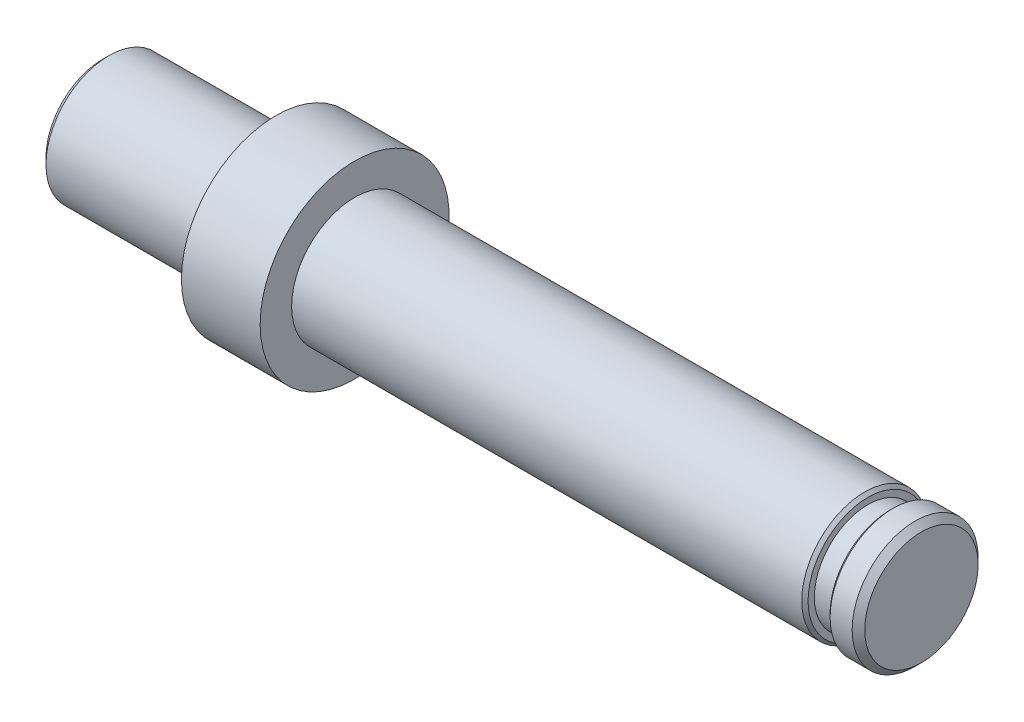
SolidWorks part; units mm, degrees
ref_plane "Спереди" through (0, 0, 0) normal (0, 0, 1) x (1, 0, 0)
ref_plane "Сверху" through (0, 0, 0) normal (0, 1, 0) x (1, 0, 0)
ref_plane "Справа" through (0, 0, 0) normal (1, 0, 0) x (0, 0, -1)
sketch "Эскиз1" plane through (0, 0, 0) normal (0, 0, 1) x (1, 0, 0)
  line L0 (0, 0) -> (26, 0)
  line L1 (26, 0) -> (26, 2)
  line L2 (26, 2) -> (25, 2)
  line L3 (25, 2) -> (25, 1.7)
  line L4 (25, 1.7) -> (24.3, 1.7)
  line L5 (24.3, 1.7) -> (24.3, 2)
  line L6 (24.3, 2) -> (8, 2)
  line L7 (8, 2) -> (8, 3)
  line L8 (8, 3) -> (5.5, 3)
  line L9 (5.5, 3) -> (5.5, 2)
  line L10 (5.5, 2) -> (0, 2)
  line L11 (0, 2) -> (0, 0)
  point P9 (22.1191, 1.3889)
  point P14 (22.1191, 0.8408)
  point P15 (22.775, 0.8408)
  point P16 (22.775, 1.3889)
  dimension "D1" = 2
  dimension "D2" = 5.5
  dimension "D3" = 3
  dimension "D4" = 1
  dimension "D5" = 2
  dimension "D6" = 2
  dimension "D7" = 26
  dimension "D8" = 1
  dimension "D9" = 0.7
  dimension "D10" = 1.7
  dimension "D11" = 2.5
revolve "Повернуть1" add sketch "Эскиз1" angle 360 about L0
chamfer "Фаска1" distance 0.2 angle 45 2 edges at (0, 0, 2) (26, 0, 2)
chamfer "Фаска2" distance 0.1 angle 45 2 edges at (25, 0, 2) (24.3, 0, 2)
